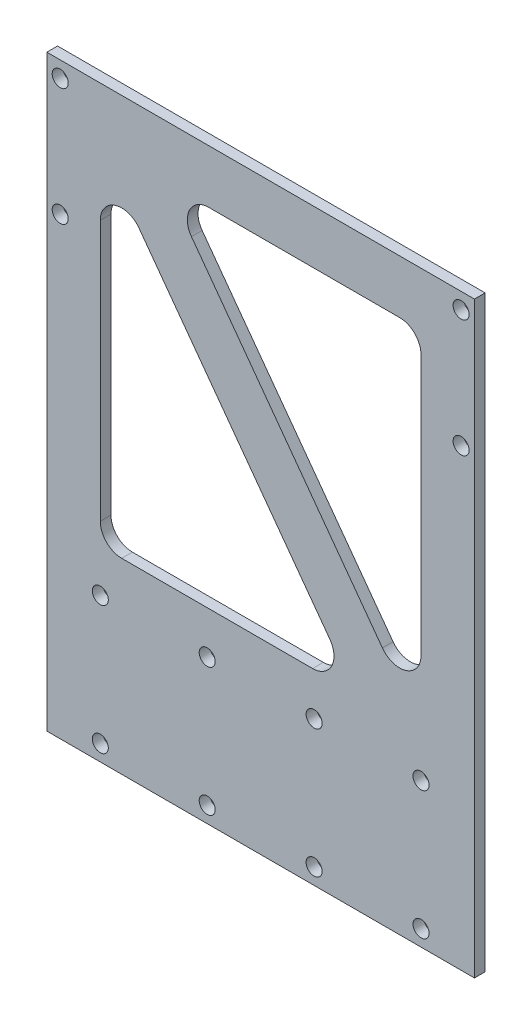
SolidWorks part; units mm, degrees
ref_plane "前视基准面" through (0, 0, 0) normal (0, 0, 1) x (1, 0, 0)
ref_plane "上视基准面" through (0, 0, 0) normal (0, 1, 0) x (1, 0, 0)
ref_plane "右视基准面" through (0, 0, 0) normal (1, 0, 0) x (0, 0, -1)
sketch "草图1" plane through (0, 0, 0) normal (0, 0, 1) x (1, 0, 0)
  line L0 (40, 0) -> (40, 110) construction
  line L1 (0, 0) -> (80, 0)
  line L2 (0, 0) -> (0, 110)
  line L3 (0, 110) -> (80, 110)
  line L4 (80, 0) -> (80, 110)
  line L5 (10, 3) -> (30, 3) construction
  line L6 (2.5, 107) -> (2.5, 85) construction
  circle A0 centre (10, 3) radius 1.5
  circle A1 centre (30, 3) radius 1.5
  circle A2 centre (50, 3) radius 1.5
  circle A3 centre (70, 3) radius 1.5
  circle A4 centre (2.5, 107) radius 1.5
  circle A5 centre (2.5, 85) radius 1.5
  circle A6 centre (77.5, 85) radius 1.5
  circle A7 centre (77.5, 107) radius 1.5
  circle A8 centre (10, 27) radius 1.5
  circle A9 centre (30, 27) radius 1.5
  circle A10 centre (50, 27) radius 1.5
  circle A11 centre (70, 27) radius 1.5
  dimension "D3" = 3
  dimension "D4" = 75
  dimension "D6" = 3
  dimension "D7" = 20
  dimension "D10" = 3
  dimension "D13" = 24
  dimension "D2" = 20
  dimension "D5" = 22
  dimension "D8" = 3
  dimension "D9" = 80
  dimension "D11" = 110
  dimension "D1" = 2
  dimension "D12" = 2
extrude "凸台-拉伸1" add sketch "草图1" along normal blind 2
sketch "草图3" plane through (0, 0, 2) normal (0, 0, 1) x (1, 0, 0)
  line L0 (10, 100) -> (10, 35)
  line L1 (10, 35) -> (57.6049, 35)
  line L2 (57.6049, 35) -> (10, 100)
  line L3 (22.3951, 100) -> (70, 35)
  line L4 (70, 35) -> (70, 100)
  line L5 (70, 100) -> (22.3951, 100)
  line L6 (80, 110) -> (0, 110) construction
  line L7 (0, 0) -> (80, 0) construction
  line L8 (80, 0) -> (80, 110) construction
  line L9 (0, 110) -> (0, 0) construction
  dimension "D1" = 10
  dimension "D2" = 35
  dimension "D3" = 10
  dimension "D4" = 10
  dimension "D5" = 10
extrude "切除-拉伸1" cut sketch "草图3" against normal blind 10
fillet "圆角1" radius 4 6 edges at (70, 35, 1) (22.3951, 100, 1) (70, 100, 1) (57.6049, 35, 1) (10, 35, 1) (10, 100, 1)
